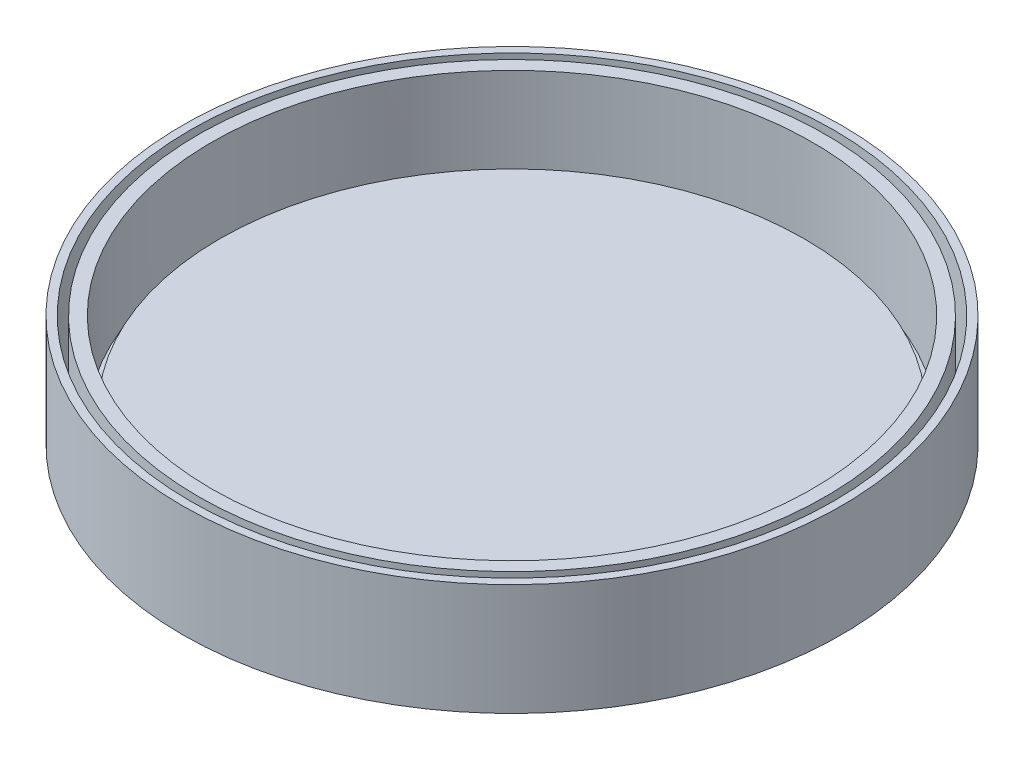
SolidWorks part; units mm, degrees
ref_plane "Front Plane" through (0, 0, 0) normal (0, 0, 1) x (1, 0, 0)
ref_plane "Top Plane" through (0, 0, 0) normal (0, 1, 0) x (1, 0, 0)
ref_plane "Right Plane" through (0, 0, 0) normal (1, 0, 0) x (0, 0, -1)
sketch "Sketch2" plane through (0, 0, 0) normal (0, 1, 0) x (1, 0, 0)
  circle A0 centre (0, 0) radius 55
  circle A1 centre (0, 0) radius 56.5
  circle A2 centre (0, 0) radius 59
  circle A3 centre (0, 0) radius 60.5
  circle A4 centre (0, 0) radius 62
extrude "Boss-Extrude1" add sketch "Sketch2" along normal blind 20 and the other way blind 1 contours A4 | A3 | A2 | A1 | A0
sketch "Sketch6" plane through (0, 20, 0) normal (0, 1, 0) x (1, 0, 0)
  circle A0 centre (0, 0) radius 55
extrude "Cut-Extrude1" cut sketch "Sketch6" against normal blind 15
sketch "Sketch7" plane through (0, -1, 0) normal (0, -1, 0) x (1, 0, 0)
  circle A0 centre (0, 0) radius 55
  circle A1 centre (0, 0) radius 56.5
extrude "Boss-Extrude3" add sketch "Sketch7" against normal blind 3.0807
